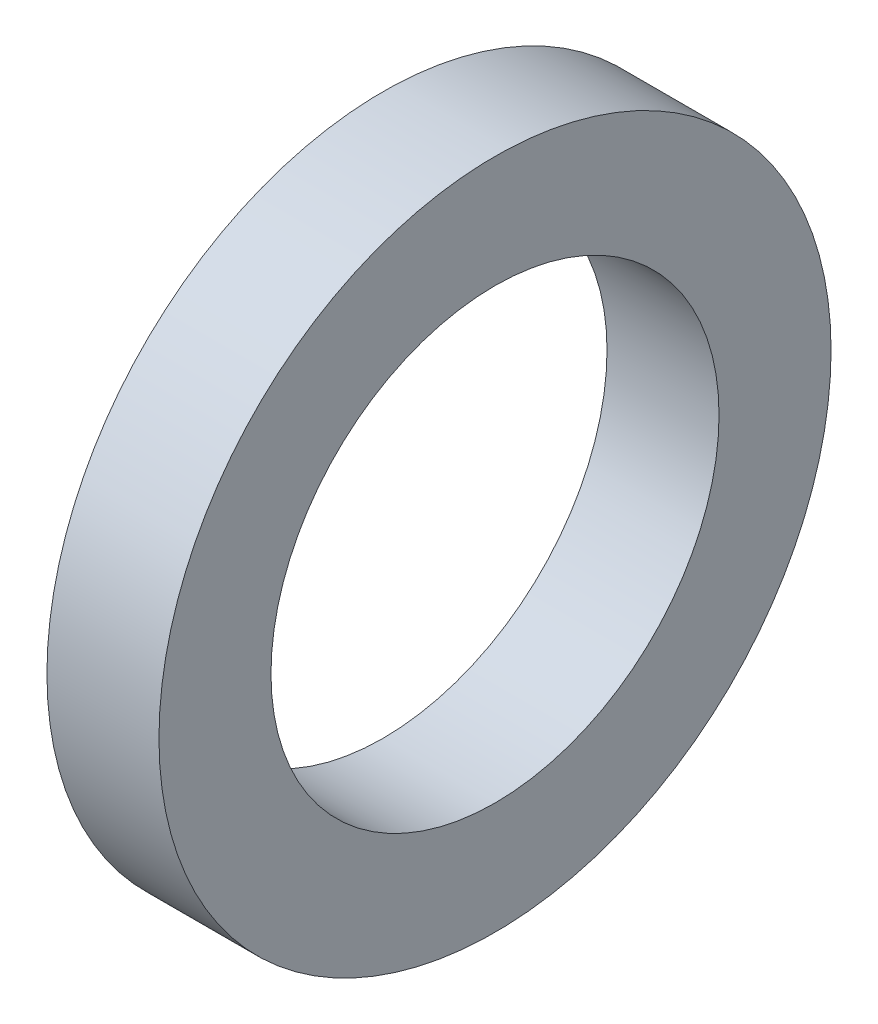
SolidWorks part; units mm, degrees
ref_plane "Front" through (0, 0, 0) normal (0, 0, 1) x (1, 0, 0)
ref_plane "Top" through (0, 0, 0) normal (0, 1, 0) x (1, 0, 0)
ref_plane "Right" through (0, 0, 0) normal (1, 0, 0) x (0, 0, -1)
sketch "Sketch1" plane through (0, 0, 0) normal (1, 0, 0) x (0, 0, -1)
  circle A0 centre (0, 0) radius 2
  circle A1 centre (0, 0) radius 3
extrude "Boss-Extrude1" add sketch "Sketch1" along normal blind 1
